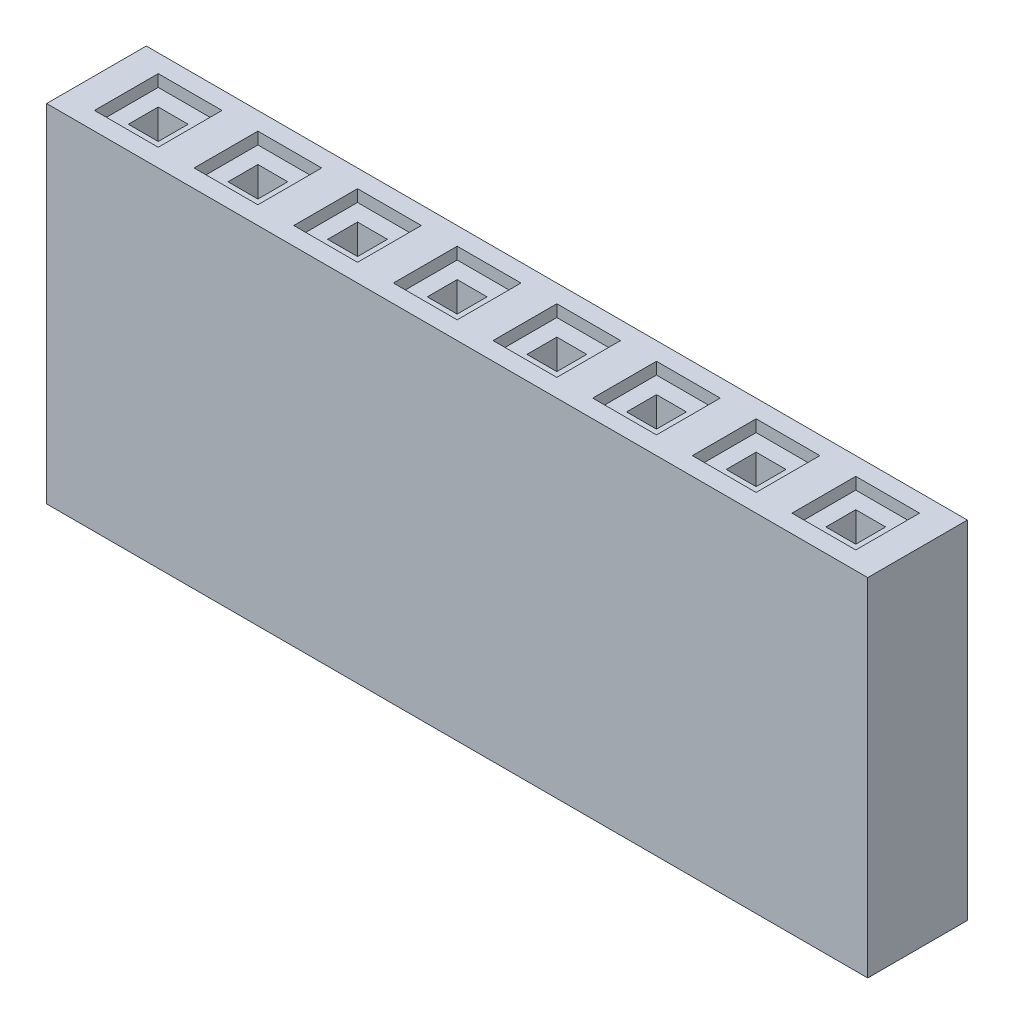
SolidWorks part; units mm, degrees
ref_plane "Alzado" through (0, 0, 0) normal (0, 0, 1) x (1, 0, 0)
ref_plane "Planta" through (0, 0, 0) normal (0, 1, 0) x (1, 0, 0)
ref_plane "Vista lateral" through (0, 0, 0) normal (1, 0, 0) x (0, 0, -1)
sketch "Croquis1" plane through (0, 0, 0) normal (0, 1, 0) x (1, 0, 0)
  line L1 (-10.3, 1.25) -> (10.3, 1.25)
  line L2 (-10.3, 1.25) -> (-10.3, -1.25)
  line L3 (-10.3, -1.25) -> (10.3, -1.25)
  line L4 (10.3, 1.25) -> (10.3, -1.25)
  line L5 (-10.3, 1.25) -> (10.3, -1.25) construction
  line L6 (-10.3, -1.25) -> (10.3, 1.25) construction
  point P0 (0, 0)
  dimension "D1" = 20.6
  dimension "D2" = 2.5
extrude "Saliente-Extruir1" add sketch "Croquis1" along normal blind 8.7
sketch "Croquis3" plane through (0, 8.7, 0) normal (0, 1, 0) x (1, 0, 0)
  line L0 (-10.3, 0.8) -> (-9.55, 0.8) construction
  line L1 (-10.3, 1.25) -> (-10.3, -1.25) construction
  line L2 (-9.55, 0.8) -> (-9.55, 1.25) construction
  line L3 (10.3, 1.25) -> (-10.3, 1.25) construction
  line L4 (-9.55, 0.8) -> (-7.95, -0.8) construction
  line L5 (-9.55, 0.8) -> (-7.95, 0.8)
  line L6 (-9.55, 0.8) -> (-9.55, -0.8)
  line L7 (-9.55, -0.8) -> (-7.95, -0.8)
  line L8 (-7.95, 0.8) -> (-7.95, -0.8)
  line L9 (-7.95, 0.8) -> (-9.55, -0.8) construction
  line L10 (-7.05, 0.8) -> (-7.05, -0.8)
  line L11 (-9.125, 0.375) -> (-8.375, 0.375)
  line L12 (-9.125, 0.375) -> (-9.125, -0.375)
  line L13 (-9.125, -0.375) -> (-8.375, -0.375)
  line L14 (-8.375, 0.375) -> (-8.375, -0.375)
  line L15 (-9.125, 0.375) -> (-8.375, -0.375) construction
  line L16 (-9.125, -0.375) -> (-8.375, 0.375) construction
  line L17 (-7.05, 0.8) -> (-5.45, 0.8)
  line L18 (-5.45, 0.8) -> (-5.45, -0.8)
  line L19 (-7.05, -0.8) -> (-5.45, -0.8)
  line L20 (-6.625, 0.375) -> (-6.625, -0.375)
  line L21 (-6.625, 0.375) -> (-5.875, 0.375)
  line L22 (-5.875, 0.375) -> (-5.875, -0.375)
  line L23 (-6.625, -0.375) -> (-5.875, -0.375)
  line L24 (-4.55, 0.8) -> (-4.55, -0.8)
  line L25 (-4.55, 0.8) -> (-2.95, 0.8)
  line L26 (-2.95, 0.8) -> (-2.95, -0.8)
  line L27 (-4.55, -0.8) -> (-2.95, -0.8)
  line L28 (-4.125, 0.375) -> (-4.125, -0.375)
  line L29 (-4.125, 0.375) -> (-3.375, 0.375)
  line L30 (-3.375, 0.375) -> (-3.375, -0.375)
  line L31 (-4.125, -0.375) -> (-3.375, -0.375)
  line L32 (-2.05, 0.8) -> (-2.05, -0.8)
  line L33 (-2.05, 0.8) -> (-0.45, 0.8)
  line L34 (-0.45, 0.8) -> (-0.45, -0.8)
  line L35 (-2.05, -0.8) -> (-0.45, -0.8)
  line L36 (-1.625, 0.375) -> (-1.625, -0.375)
  line L37 (-1.625, 0.375) -> (-0.875, 0.375)
  line L38 (-0.875, 0.375) -> (-0.875, -0.375)
  line L39 (-1.625, -0.375) -> (-0.875, -0.375)
  line L40 (0.45, 0.8) -> (0.45, -0.8)
  line L41 (0.45, 0.8) -> (2.05, 0.8)
  line L42 (2.05, 0.8) -> (2.05, -0.8)
  line L43 (0.45, -0.8) -> (2.05, -0.8)
  line L44 (0.875, 0.375) -> (0.875, -0.375)
  line L45 (0.875, 0.375) -> (1.625, 0.375)
  line L46 (1.625, 0.375) -> (1.625, -0.375)
  line L47 (0.875, -0.375) -> (1.625, -0.375)
  line L48 (2.95, 0.8) -> (2.95, -0.8)
  line L49 (2.95, 0.8) -> (4.55, 0.8)
  line L50 (4.55, 0.8) -> (4.55, -0.8)
  line L51 (2.95, -0.8) -> (4.55, -0.8)
  line L52 (3.375, 0.375) -> (3.375, -0.375)
  line L53 (3.375, 0.375) -> (4.125, 0.375)
  line L54 (4.125, 0.375) -> (4.125, -0.375)
  line L55 (3.375, -0.375) -> (4.125, -0.375)
  line L56 (5.45, 0.8) -> (5.45, -0.8)
  line L57 (5.45, 0.8) -> (7.05, 0.8)
  line L58 (7.05, 0.8) -> (7.05, -0.8)
  line L59 (5.45, -0.8) -> (7.05, -0.8)
  line L60 (5.875, 0.375) -> (5.875, -0.375)
  line L61 (5.875, 0.375) -> (6.625, 0.375)
  line L62 (6.625, 0.375) -> (6.625, -0.375)
  line L63 (5.875, -0.375) -> (6.625, -0.375)
  line L64 (7.95, 0.8) -> (7.95, -0.8)
  line L65 (7.95, 0.8) -> (9.55, 0.8)
  line L66 (9.55, 0.8) -> (9.55, -0.8)
  line L67 (7.95, -0.8) -> (9.55, -0.8)
  line L68 (8.375, 0.375) -> (8.375, -0.375)
  line L69 (8.375, 0.375) -> (9.125, 0.375)
  line L70 (9.125, 0.375) -> (9.125, -0.375)
  line L71 (8.375, -0.375) -> (9.125, -0.375)
  point P10 (-8.75, 0)
  dimension "D1" = 0.75
  dimension "D2" = 0.45
  dimension "D3" = 1.6
  dimension "D4" = 1.6
  dimension "D5" = 0.75
  dimension "D6" = 0.75
  dimension "D7" = 8
extrude "Cortar-Extruir1" cut sketch "Croquis3" against normal blind 8.5 contours L8 L5 L6 L7 L11 L14 L13 L12 | L10 L19 L18 L17 L23 L20 L21 L22 | L24 L27 L26 L25 L31 L28 L29 L30 | L32 L35 L34 L33 L39 L36 L37 L38 | L40 L43 L42 L41 L47 L44 L45 L46 | L48 L51 L50 L49 L55 L52 L53 L54 | L56 L59 L58 L57 L63 L60 L61 L62 | L64 L67 L66 L65 L71 L68 L69 L70
sketch "Croquis5" plane through (0, 0.2, 0) normal (0, 1, 0) x (1, 0, 0)
  line L0 (-9.55, 0.8) -> (-7.95, -0.8) construction
  line L1 (-7.95, 0.8) -> (-9.55, -0.8) construction
  line L2 (-7.05, 0.8) -> (-5.45, -0.8) construction
  line L3 (-9.125, 0.375) -> (-8.375, 0.375)
  line L4 (-9.125, 0.375) -> (-9.125, -0.375)
  line L5 (-9.125, -0.375) -> (-8.375, -0.375)
  line L6 (-8.375, 0.375) -> (-8.375, -0.375)
  line L7 (-9.125, 0.375) -> (-8.375, -0.375) construction
  line L8 (-9.125, -0.375) -> (-8.375, 0.375) construction
  line L9 (-5.45, 0.8) -> (-7.05, -0.8) construction
  line L10 (-6.625, 0.375) -> (-6.625, -0.375)
  line L11 (-6.625, 0.375) -> (-5.875, 0.375)
  line L12 (-6.625, 0.375) -> (-6.625, -0.375)
  line L13 (-6.625, -0.375) -> (-5.875, -0.375)
  line L14 (-5.875, 0.375) -> (-5.875, -0.375)
  line L15 (-6.625, 0.375) -> (-5.875, -0.375) construction
  line L16 (-6.625, -0.375) -> (-5.875, 0.375) construction
  line L17 (-6.625, 0.375) -> (-5.875, 0.375)
  line L18 (-5.875, 0.375) -> (-5.875, -0.375)
  line L19 (-6.625, -0.375) -> (-5.875, -0.375)
  line L20 (-4.125, 0.375) -> (-4.125, -0.375)
  line L21 (-4.125, 0.375) -> (-3.375, 0.375)
  line L22 (-3.375, 0.375) -> (-3.375, -0.375)
  line L23 (-4.125, -0.375) -> (-3.375, -0.375)
  line L24 (-4.125, 0.375) -> (-4.125, -0.375)
  line L25 (-4.125, 0.375) -> (-3.375, 0.375)
  line L26 (-3.375, 0.375) -> (-3.375, -0.375)
  line L27 (-4.125, -0.375) -> (-3.375, -0.375)
  line L28 (-1.625, 0.375) -> (-1.625, -0.375)
  line L29 (-1.625, 0.375) -> (-0.875, 0.375)
  line L30 (-0.875, 0.375) -> (-0.875, -0.375)
  line L31 (-1.625, -0.375) -> (-0.875, -0.375)
  line L32 (-1.625, 0.375) -> (-1.625, -0.375)
  line L33 (-1.625, 0.375) -> (-0.875, 0.375)
  line L34 (-0.875, 0.375) -> (-0.875, -0.375)
  line L35 (-1.625, -0.375) -> (-0.875, -0.375)
  line L36 (0.875, 0.375) -> (0.875, -0.375)
  line L37 (0.875, 0.375) -> (1.625, 0.375)
  line L38 (1.625, 0.375) -> (1.625, -0.375)
  line L39 (0.875, -0.375) -> (1.625, -0.375)
  line L40 (0.875, 0.375) -> (0.875, -0.375)
  line L41 (0.875, 0.375) -> (1.625, 0.375)
  line L42 (1.625, 0.375) -> (1.625, -0.375)
  line L43 (0.875, -0.375) -> (1.625, -0.375)
  line L44 (3.375, 0.375) -> (3.375, -0.375)
  line L45 (3.375, 0.375) -> (4.125, 0.375)
  line L46 (4.125, 0.375) -> (4.125, -0.375)
  line L47 (3.375, -0.375) -> (4.125, -0.375)
  line L48 (3.375, 0.375) -> (3.375, -0.375)
  line L49 (3.375, 0.375) -> (4.125, 0.375)
  line L50 (4.125, 0.375) -> (4.125, -0.375)
  line L51 (3.375, -0.375) -> (4.125, -0.375)
  line L52 (5.875, 0.375) -> (5.875, -0.375)
  line L53 (5.875, 0.375) -> (6.625, 0.375)
  line L54 (6.625, 0.375) -> (6.625, -0.375)
  line L55 (5.875, -0.375) -> (6.625, -0.375)
  line L56 (5.875, 0.375) -> (5.875, -0.375)
  line L57 (5.875, 0.375) -> (6.625, 0.375)
  line L58 (6.625, 0.375) -> (6.625, -0.375)
  line L59 (5.875, -0.375) -> (6.625, -0.375)
  line L60 (8.375, 0.375) -> (8.375, -0.375)
  line L61 (8.375, 0.375) -> (9.125, 0.375)
  line L62 (9.125, 0.375) -> (9.125, -0.375)
  line L63 (8.375, -0.375) -> (9.125, -0.375)
  line L65 (-9.55, 0.8) -> (-7.95, 0.8)
  line L66 (-9.55, 0.8) -> (-9.55, -0.8)
  line L67 (-9.55, -0.8) -> (-7.95, -0.8)
  line L68 (-7.95, 0.8) -> (-7.95, -0.8)
  line L69 (-7.05, 0.8) -> (-5.45, 0.8)
  line L70 (-7.05, 0.8) -> (-7.05, -0.8)
  line L71 (-7.05, -0.8) -> (-5.45, -0.8)
  line L72 (-5.45, 0.8) -> (-5.45, -0.8)
  line L73 (-4.55, 0.8) -> (-2.95, 0.8)
  line L74 (-4.55, 0.8) -> (-4.55, -0.8)
  line L75 (-4.55, -0.8) -> (-2.95, -0.8)
  line L76 (-2.95, 0.8) -> (-2.95, -0.8)
  line L77 (-2.05, 0.8) -> (-0.45, 0.8)
  line L78 (-2.05, 0.8) -> (-2.05, -0.8)
  line L79 (-2.05, -0.8) -> (-0.45, -0.8)
  line L80 (-0.45, 0.8) -> (-0.45, -0.8)
  line L81 (0.45, 0.8) -> (2.05, 0.8)
  line L82 (0.45, 0.8) -> (0.45, -0.8)
  line L83 (0.45, -0.8) -> (2.05, -0.8)
  line L84 (2.05, 0.8) -> (2.05, -0.8)
  line L85 (2.95, 0.8) -> (4.55, 0.8)
  line L86 (2.95, 0.8) -> (2.95, -0.8)
  line L87 (2.95, -0.8) -> (4.55, -0.8)
  line L88 (4.55, 0.8) -> (4.55, -0.8)
  line L89 (5.45, 0.8) -> (7.05, 0.8)
  line L90 (5.45, 0.8) -> (5.45, -0.8)
  line L91 (5.45, -0.8) -> (7.05, -0.8)
  line L92 (7.05, 0.8) -> (7.05, -0.8)
  line L93 (7.95, 0.8) -> (9.55, 0.8)
  line L94 (7.95, 0.8) -> (7.95, -0.8)
  line L95 (7.95, -0.8) -> (9.55, -0.8)
  line L96 (9.55, 0.8) -> (9.55, -0.8)
  point P8 (-8.75, 0)
  point P21 (-6.25, 0)
  dimension "D1" = 0.75
  dimension "D2" = 0.75
  dimension "D3" = 0.75
  dimension "D4" = 0.75
  dimension "D5" = 7
extrude "Saliente-Extruir2" add sketch "Croquis5" along normal blind 8.2 contours L6 L3 L4 L5 | L72 L69 L70 L71 L11 L14 L13 L10 | L76 L73 L74 L75 L23 L20 L21 L22 | L80 L77 L78 L79 L31 L28 L29 L30 | L84 L81 L82 L83 L39 L36 L37 L38 | L96 L93 L94 L95 L63 L60 L61 L62 | L52 L55 L54 L53 | L44 L47 L46 L45 | L66 L65 L68 L67 | L88 L87 L86 L85 | L90 L91 L92 L89
